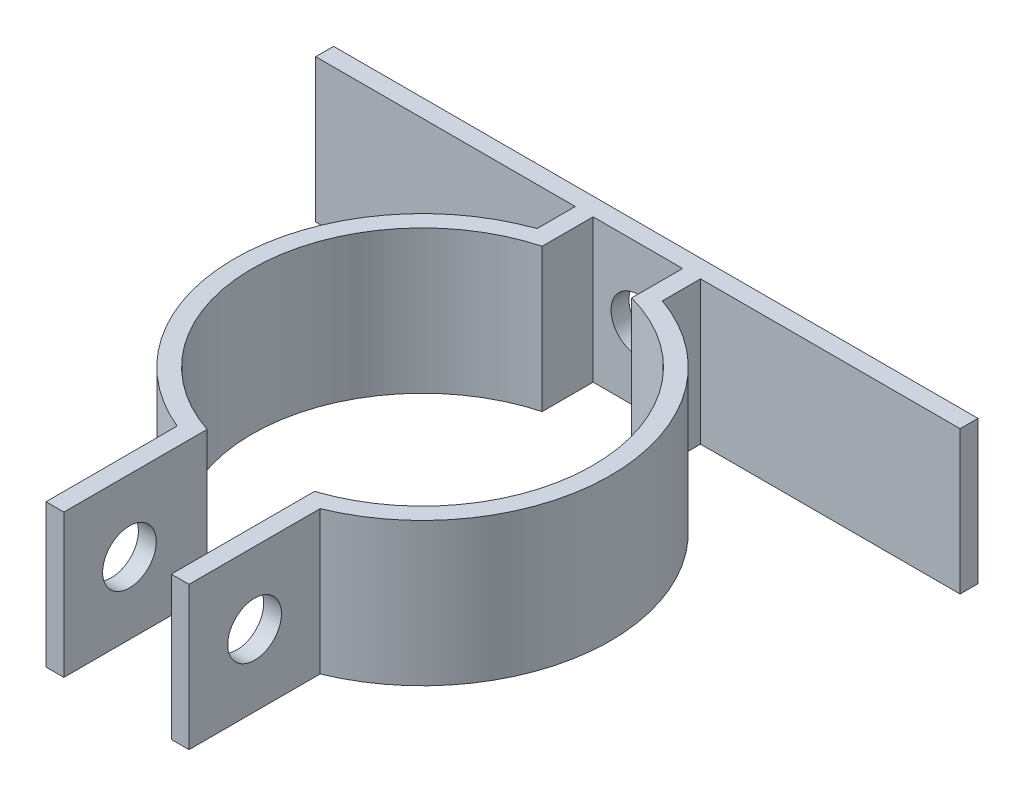
SolidWorks part; units mm, degrees
ref_plane "Front Plane" through (0, 0, 0) normal (0, 0, 1) x (1, 0, 0)
ref_plane "Top Plane" through (0, 0, 0) normal (0, 1, 0) x (1, 0, 0)
ref_plane "Right Plane" through (0, 0, 0) normal (1, 0, 0) x (0, 0, -1)
sketch "Sketch1" plane through (0, 0, 0) normal (0, 1, 0) x (1, 0, 0)
  line L0 (0, 0) -> (0, 3.175)
  line L1 (0, 3.175) -> (114.3, 3.175)
  line L2 (114.3, 3.175) -> (114.3, 0)
  line L3 (114.3, 0) -> (68.2625, 0)
  line L4 (0, 0) -> (46.0375, 0)
  line L5 (49.2125, 0) -> (49.2125, -9.0398)
  line L6 (49.2125, 0) -> (65.0875, 0)
  line L7 (46.0375, -6.7741) -> (46.0375, 0)
  line L8 (65.0875, 0) -> (65.0875, -9.0398)
  line L9 (44.45, -69.0287) -> (44.45, -92.291)
  line L10 (68.2625, -6.7741) -> (68.2625, 0)
  line L11 (47.625, -66.891) -> (47.625, -92.291)
  line L12 (44.45, -92.291) -> (47.625, -92.291)
  line L13 (69.8246, -69.0391) -> (69.8246, -92.291)
  line L14 (66.675, -66.891) -> (66.675, -92.291)
  line L15 (69.8246, -92.291) -> (66.675, -92.291)
  line L16 (57.15, 3.175) -> (57.15, -122.2617) construction
  arc A0 (69.8246, -69.0391) -> (68.2625, -6.7741) centre (57.15, -38.205) ccw
  arc A1 (49.2125, -9.0398) -> (47.625, -66.891) centre (57.15, -38.205) ccw
  arc A2 (46.0375, -6.7741) -> (44.45, -69.0287) centre (57.15, -38.205) ccw
  arc A3 (66.675, -66.891) -> (65.0875, -9.0398) centre (57.15, -38.205) ccw
  point P23 (57.15, 0)
  dimension "D4" = 3.175
  dimension "D8" = 60.452
  dimension "D6" = 33.3375
  dimension "D9" = 30.226
  dimension "D1" = 3.175
  dimension "D2" = 3.175
  dimension "D3" = 114.3
  dimension "D5" = 3.175
  dimension "D7" = 15.875
  dimension "D10" = 9.0398
  dimension "D11" = 3.175
  dimension "D12" = 3.1496
  dimension "D13" = 19.05
  dimension "D14" = 9.525
  dimension "D15" = 25.4
extrude "Boss-Extrude1" add sketch "Sketch1" along normal blind 25.4
sketch "Sketch2" plane through (69.8246, 0, 0) normal (1, 0, 0) x (0, 0, -1)
  circle A0 centre (-80.665, 12.7) radius 4.7625
  dimension "D1" = 9.525
extrude "Cut-Extrude1" cut sketch "Sketch2" against normal blind 25.4
sketch "Sketch3" plane through (0, 0, -3.175) normal (0, 0, -1) x (-1, 0, 0)
  circle A0 centre (-57.15, 12.7) radius 4.7625
  dimension "D1" = 9.525
extrude "Cut-Extrude2" cut sketch "Sketch3" against normal blind 25.4
